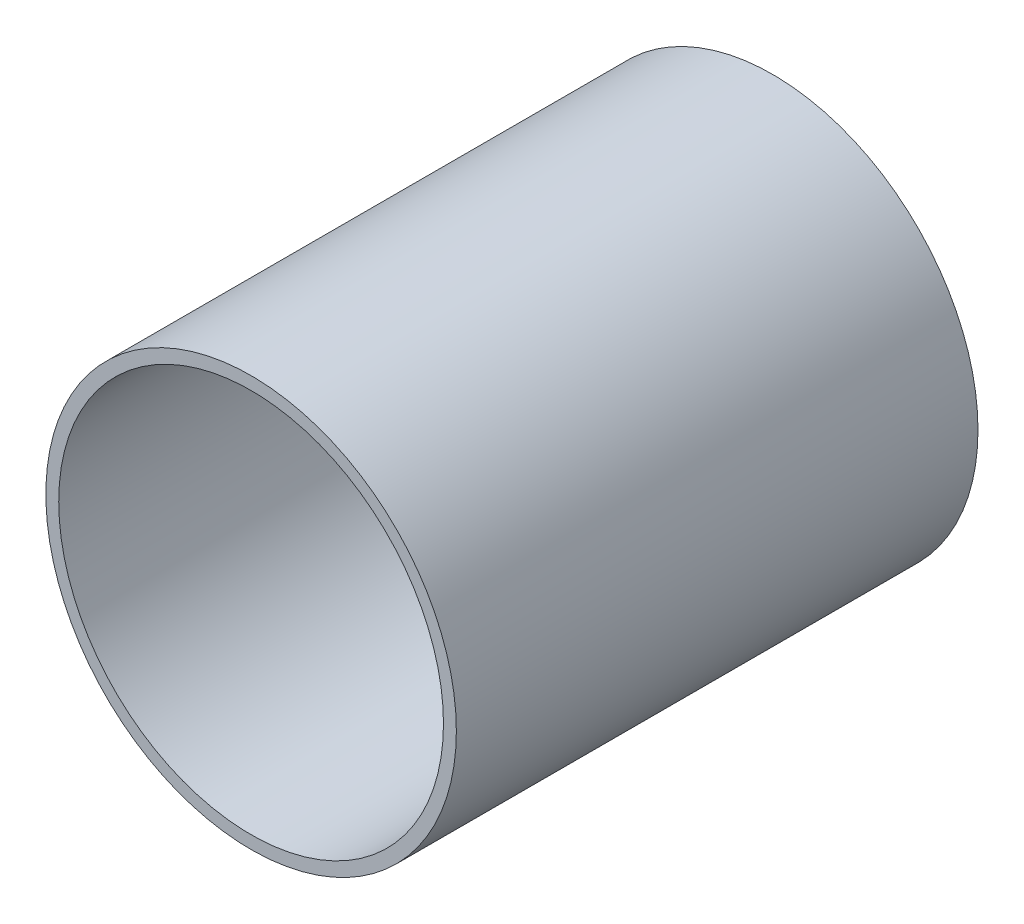
SolidWorks part; units mm, degrees
ref_plane "Alzado" through (0, 0, 0) normal (0, 0, 1) x (1, 0, 0)
ref_plane "Planta" through (0, 0, 0) normal (0, 1, 0) x (1, 0, 0)
ref_plane "Vista lateral" through (0, 0, 0) normal (1, 0, 0) x (0, 0, -1)
sketch "Croquis1" plane through (0, 0, 0) normal (0, 0, 1) x (1, 0, 0)
  circle A0 centre (0, 0) radius 31.88
  dimension "D1" = 63.76
extrude "Saliente-Extruir1" add sketch "Croquis1" along normal mid plane 81.02
sketch "Croquis2" plane through (0, 0, -40.51) normal (0, 0, -1) x (-1, 0, 0)
  circle A0 centre (0, 0) radius 29.88
  circle A1 centre (0, 0) radius 31.88 construction
  dimension "D1" = 2
extrude "Cortar-Extruir1" cut sketch "Croquis2" against normal blind 81.02
